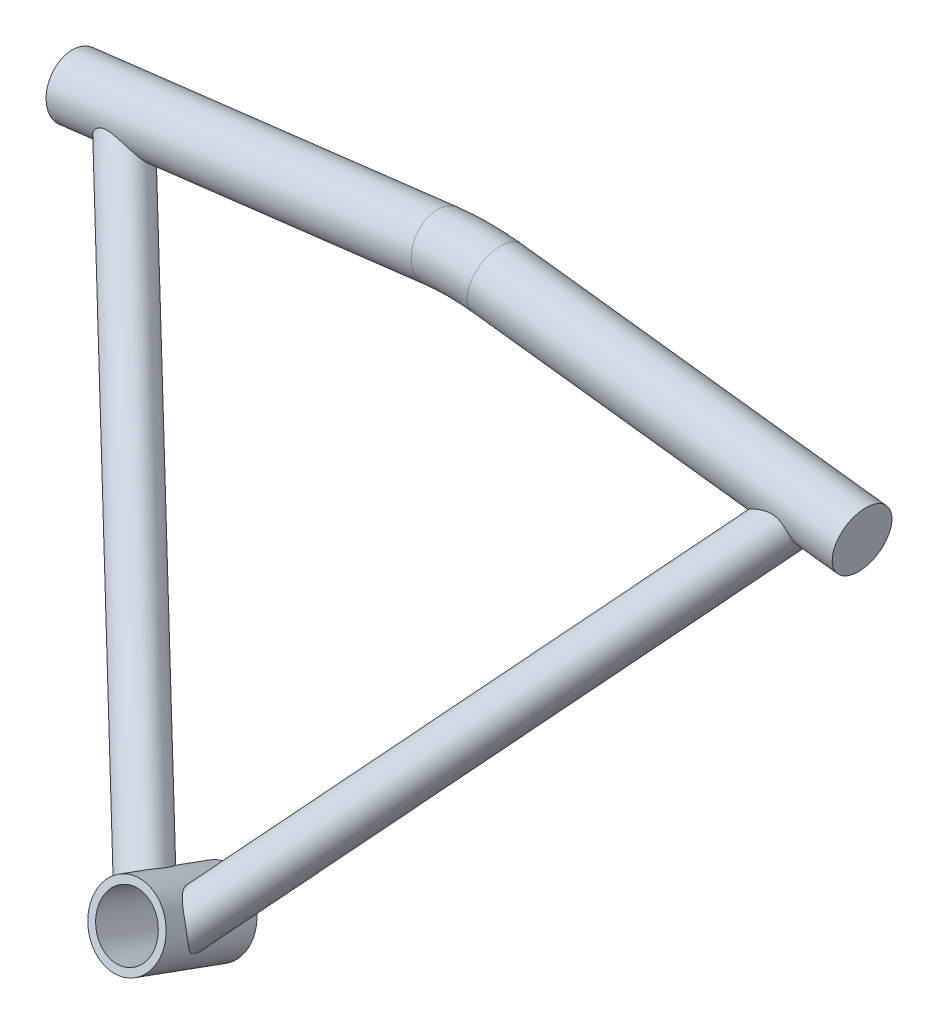
SolidWorks part; units mm, degrees
material "AISI 4130 Steel, normalized at 870C"
ref_plane "Front Plane" through (0, 0, 0) normal (0, 0, 1) x (1, 0, 0)
ref_plane "Top Plane" through (0, 0, 0) normal (0, 1, 0) x (1, 0, 0)
ref_plane "Right Plane" through (0, 0, 0) normal (1, 0, 0) x (0, 0, -1)
sketch "Sketch3" plane through (0, 0, 0) normal (0, 1, 0) x (1, 0, 0)
  line L0 (-5.08, -6.35) -> (5.08, -6.35) construction
  line L2 (0, -88.2205) -> (0, 88.2205) construction
  line L3 (5.08, 0) -> (-5.08, 0) construction
  dimension "D1" = 5.08
  dimension "D2" = 10.16
  dimension "D3" = 6.35
  dimension "D4" = 10.16
  dimension "D5" = 5.08
ref_plane "Plane1" through (0, 3.1056, 3.8351) normal (0, 0.6293, 0.7771) x (1, 0, 0)
ref_plane "Plane3" through (0, 0, 0) normal (0, 0.342, 0.9397) x (-1, 0, 0)
sketch "Sketch1" plane through (0, 0, 0) normal (0, 0.342, 0.9397) x (1, 0, 0)
  circle A0 centre (0, 0) radius 15.875
  dimension "D1" = 31.75
extrude "Boss-Extrude1" add sketch "Sketch1" along normal mid plane 41.402 contours A0
sketch "Sketch4" plane through (0, 3.1056, 3.8351) normal (0, 0.6293, 0.7771) x (1, 0, 0)
  line L0 (-5.08, -3.9962) -> (-144.2743, 202.3678)
  line L2 (0, -24.1976) -> (0, 24.1976) construction
  point P2 (0, 0)
  point P4 (0, 0)
  point P7 (0, 0)
  point P8 (0, 0)
  point P9 (0, 0)
  point P10 (0, 0)
  dimension "D2" = 34
  dimension "D3" = 248.92
sweep "Sweep1" add path "Sketch4" circular profile diameter 19.05 parameters "D3"=19.05
sketch "Sketch15" plane through (0, 3.1056, 3.8351) normal (0, 0.6293, 0.7771) x (1, 0, 0)
  line L0 (5.08, -3.9962) -> (144.2743, 202.3678)
  line L1 (0, -87.5476) -> (0, 87.5476) construction
  dimension "D1" = 248.92
  dimension "D2" = 34
sweep "Sweep2" add path "Sketch15" circular profile diameter 19.05 parameters "D3"=19.05
sketch "Sketch36" plane through (-138.9302, 160.0707, -129.6227) normal (-0.5592, 0.6443, -0.5217) x (0.829, 0.4281, -0.3599)
  circle A0 centre (-6.4964, -4.8685) radius 7.9375
  dimension "D1" = 15.875
extrude "Cut-Extrude2" cut sketch "Sketch36" against normal up to surface (258.9176 mm away)
sketch "Sketch37" plane through (138.9302, 160.0707, -129.6227) normal (0.5592, 0.6443, -0.5217) x (0.829, -0.4281, 0.3599)
  circle A0 centre (6.4964, -4.8685) radius 7.9375
  dimension "D1" = 15.875
extrude "Cut-Extrude3" cut sketch "Sketch37" against normal up to surface (234.3562 mm away)
sketch "Sketch77" plane through (0, 7.0802, 19.4526) normal (0, 0.342, 0.9397) x (1, 0, 0)
  circle A1 centre (0, 0) radius 15.875
extrude "Boss-Extrude2" add sketch "Sketch77" against normal up to surface (41.402 mm away) up to face at (0, -21.9978, -14.023)
sketch "Sketch2" plane through (0, -7.0802, -19.4526) normal (0, -0.342, -0.9397) x (-1, 0, 0)
  circle A0 centre (0, 0) radius 12.7
  dimension "D1" = 25.4
extrude "Cut-Extrude1" cut sketch "Sketch2" against normal up to next
ref_plane "Plane2" through (0, 0, -127) normal (0, 0, 1) x (1, 0, 0)
sketch "Sketch40" plane through (-106.934, 0, -127) normal (0, 0, 1) x (1, 0, 0)
  line L2 (106.934, -87.5476) -> (106.934, 87.5476) construction
  line L3 (94.97, 180.1266) -> (-61.369, 161.2039)
  line L4 (118.898, 180.1266) -> (275.237, 161.2039)
  arc A0 (94.97, 180.1266) -> (118.898, 180.1266) centre (106.934, 81.28) cw
  point P0 (106.934, 180.848)
  point P7 (106.934, 180.848)
  dimension "D1" = 157.48
  dimension "D3" = 99.568
  dimension "D2" = 157.48
  dimension "D4" = 7.6
  dimension "D5" = 99.568
sweep "Sweep3" add path "Sketch40" circular profile diameter 25.4 parameters "D3"=25.4
